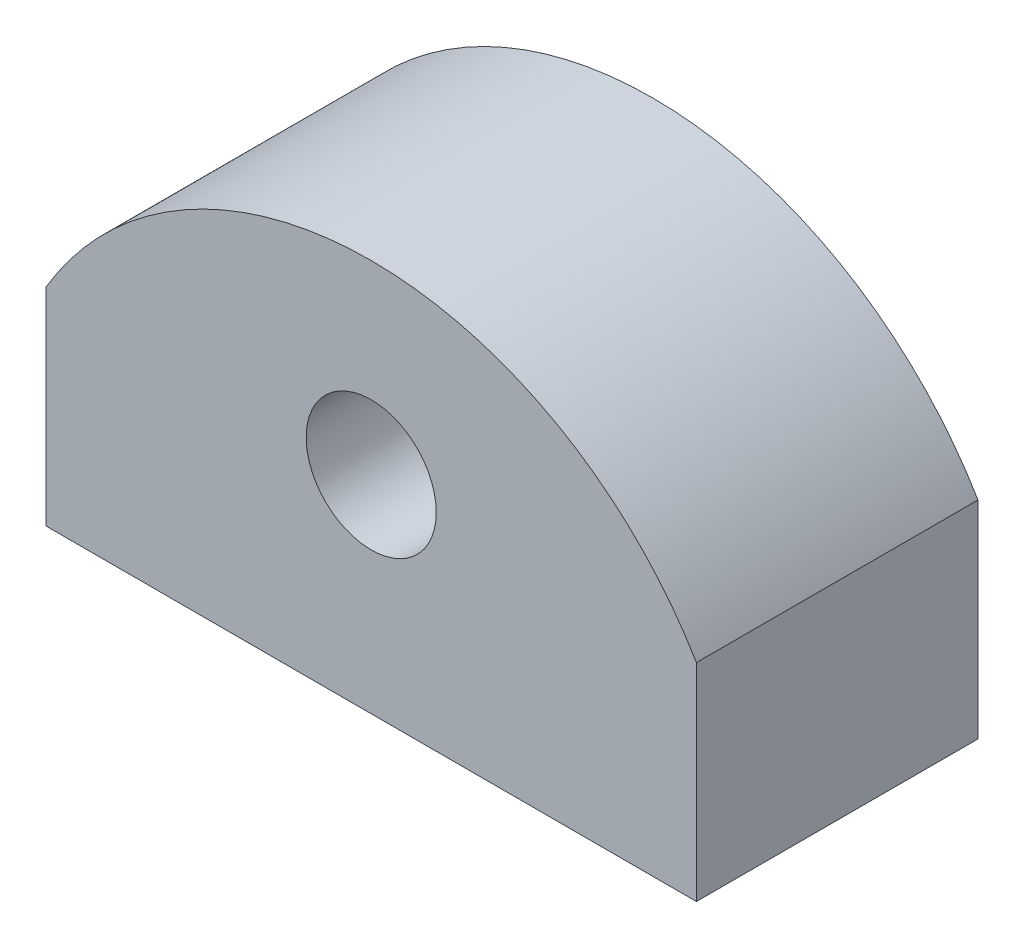
SolidWorks part; units mm, degrees
material "6061 Alloy"
ref_plane "Front Plane" through (0, 0, 0) normal (0, 0, 1) x (1, 0, 0)
ref_plane "Top Plane" through (0, 0, 0) normal (0, 1, 0) x (1, 0, 0)
ref_plane "Right Plane" through (0, 0, 0) normal (1, 0, 0) x (0, 0, -1)
sketch "Sketch1" plane through (0, 0, 0) normal (0, 0, 1) x (1, 0, 0)
  line L1 (-11, 3.5) -> (11, 3.5) construction
  line L2 (-11, 3.5) -> (-11, -3.5)
  line L3 (-11, -3.5) -> (11, -3.5)
  line L4 (11, 3.5) -> (11, -3.5)
  line L5 (0, -3.5) -> (0, -3) construction
  line L6 (-11, 0) -> (11, 0) construction
  arc A0 (-11, 3.5) -> (11, 3.5) centre (0, -3) cw
  point P0 (0, 0)
  dimension "D1" = 22
  dimension "D2" = 7
  dimension "D3" = 3
extrude "Boss-Extrude1" add sketch "Sketch1" along normal blind 9.525
sketch "Sketch2" plane through (0, 0, 9.525) normal (0, 0, 1) x (1, 0, 0)
  line L0 (-11, 3.5) -> (11, 3.5) construction
  circle A0 centre (0, 3.5) radius 2.2
  dimension "D1" = 4.4
extrude "M5_DRILL" cut sketch "Sketch2" against normal up to surface (9.525 mm away) up to face at (0, 1.5692, 0)
sketch "Sketch3" plane through (0, -3.5, 0) normal (0, -1, 0) x (1, 0, 0)
  line L0 (-11, 4.7625) -> (11, 4.7625) construction
  line L1 (-11, 9.525) -> (-11, 0) construction
  line L2 (11, 9.525) -> (11, 0) construction
  line L3 (0, 0) -> (0, 9.525) construction
  line L4 (-11, 9.525) -> (11, 9.525) construction
  circle A0 centre (-6, 4.7625) radius 1.75
  circle A1 centre (6, 4.7625) radius 1.75
  dimension "D1" = 3.5
  dimension "D2" = 6
extrude "M4_DRILL" cut sketch "Sketch3" against normal blind 8
